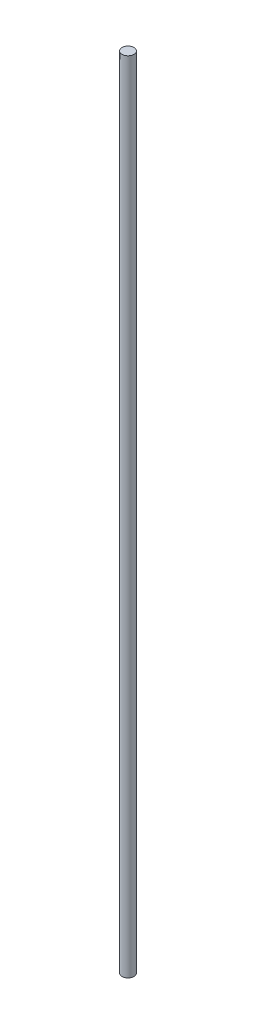
SolidWorks part; units mm, degrees
ref_plane "前视基准面" through (0, 0, 0) normal (0, 0, 1) x (1, 0, 0)
ref_plane "上视基准面" through (0, 0, 0) normal (0, 1, 0) x (1, 0, 0)
ref_plane "右视基准面" through (0, 0, 0) normal (1, 0, 0) x (0, 0, -1)
other "Configuration Table"
sketch "草图1" plane through (0, 0, 0) normal (0, 1, 0) x (1, 0, 0)
  circle A0 centre (0, 0) radius 1.5
  dimension "D1" = 3
extrude "凸台-拉伸1" add sketch "草图1" along normal blind 200
